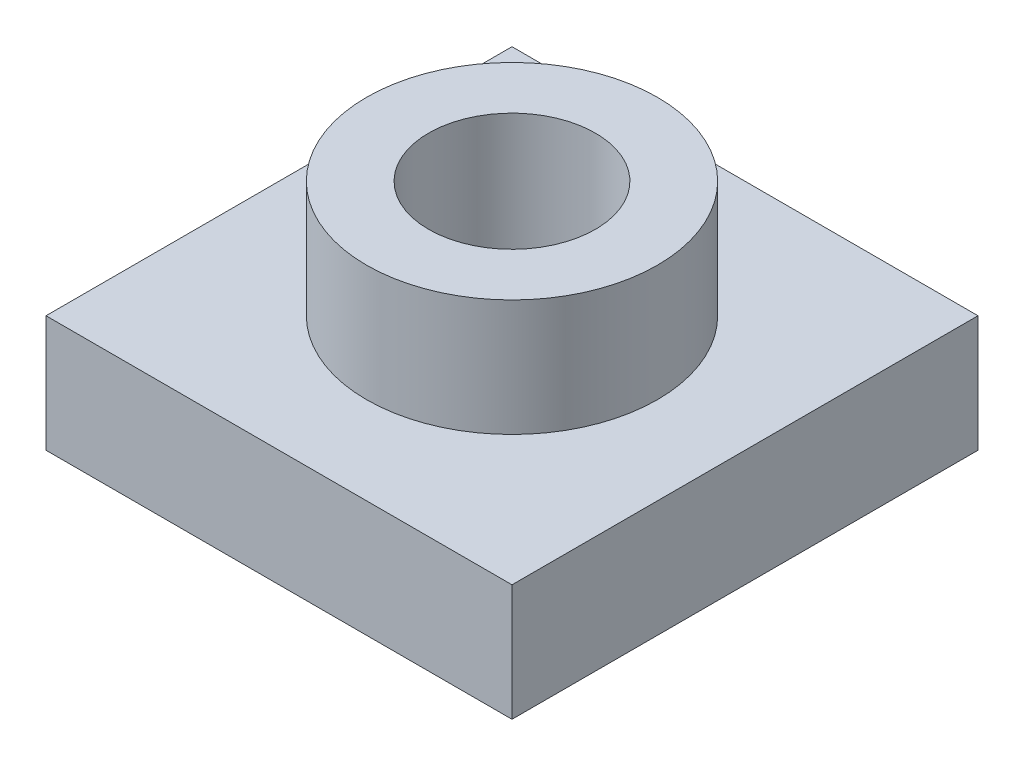
SolidWorks part; units mm, degrees
ref_plane "Front Plane" through (0, 0, 0) normal (0, 0, 1) x (1, 0, 0)
ref_plane "Top Plane" through (0, 0, 0) normal (0, 1, 0) x (1, 0, 0)
ref_plane "Right Plane" through (0, 0, 0) normal (1, 0, 0) x (0, 0, -1)
sketch "Sketch1" plane through (0, 0, 0) normal (0, 1, 0) x (1, 0, 0)
  line L1 (0, 0) -> (50, 0)
  line L2 (0, 0) -> (0, 50)
  line L3 (0, 50) -> (50, 50)
  line L4 (50, 0) -> (50, 50)
  dimension "D1" = 50
  dimension "D2" = 50
extrude "Boss-Extrude1" add sketch "Sketch1" along normal blind 12.5
sketch "Sketch2" plane through (0, 12.5, 0) normal (0, 1, 0) x (1, 0, 0)
  line L4 (0, 50) -> (0, 0) construction
  line L5 (50, 50) -> (0, 50) construction
  circle A1 centre (25, 25) radius 8.95
  circle A3 centre (25, 25) radius 15.605
  point P3 (0, 25)
  point P7 (25, 50)
  dimension "D1" = 17.9
  dimension "D2" = 31.21
extrude "Boss-Extrude2" add sketch "Sketch2" along normal blind 12.5
sketch "Sketch3" plane through (0, 25, 0) normal (0, 1, 0) x (1, 0, 0)
  circle A0 centre (25, 25) radius 8.95 construction
  circle A1 centre (25, 25) radius 8.95
extrude "Cut-Extrude1" cut sketch "Sketch3" against normal through all
